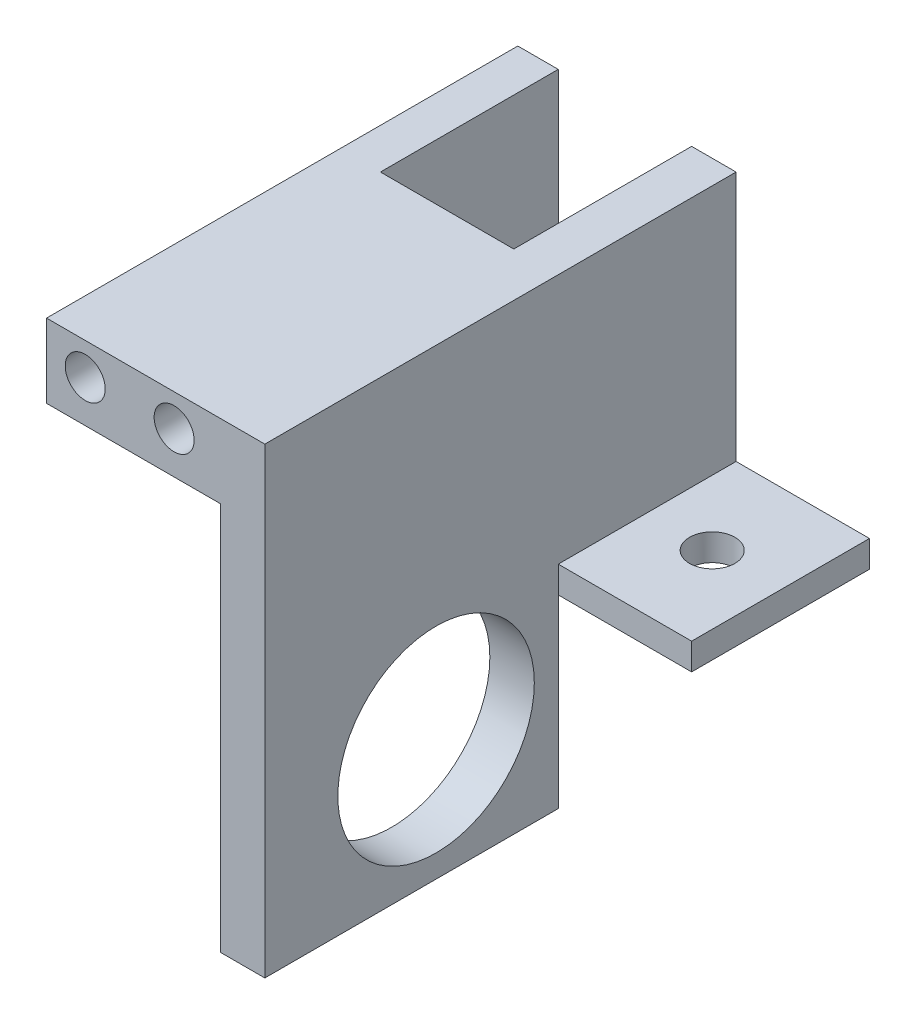
SolidWorks part; units mm, degrees
ref_plane "前视基准面" through (0, 0, 0) normal (0, 0, 1) x (1, 0, 0)
ref_plane "上视基准面" through (0, 0, 0) normal (0, 1, 0) x (1, 0, 0)
ref_plane "右视基准面" through (0, 0, 0) normal (1, 0, 0) x (0, 0, -1)
other "Configuration Table"
sketch "草图1" plane through (0, 0, 0) normal (0, 0, 1) x (1, 0, 0)
  line L1 (-11.1667, -5) -> (11.1667, -5)
  line L2 (-11.1667, -5) -> (-11.1667, 5)
  line L3 (-11.1667, 5) -> (11.1667, 5)
  line L4 (11.1667, -5) -> (11.1667, 5)
  line L5 (-11.1667, -5) -> (11.1667, 5) construction
  line L6 (-11.1667, 5) -> (11.1667, -5) construction
  point P0 (0, 0)
  dimension "D1" = 10
extrude "凸台-拉伸1" add sketch "草图1" along normal blind 30
sketch "草图2" plane through (0, -5, 0) normal (0, -1, 0) x (1, 0, 0)
  line L0 (-10.0833, 30.4566) -> (-10.0833, 0)
  line L1 (-10.0833, 30) -> (-10.0833, 38.1808) construction
  line L2 (-11.1667, 0) -> (11.1667, 0) construction
sketch "草图3" plane through (0, 0, 30) normal (0, 0, 1) x (1, 0, 0)
  line L0 (-9.2333, 0.05) -> (-9.2333, -5.0113)
  line L2 (9.4667, -5) -> (9.4667, 0.05)
  circle A0 centre (5.1167, -0.3) radius 2.25
  circle A1 centre (-4.8833, -0.3) radius 2.25
  arc A3 (9.4667, 0.05) -> (7.4667, 2.05) centre (7.4667, 0.05) ccw
  arc A4 (-9.2333, 0.05) -> (-6.4511, 1.8907) centre (-7.2333, 0.05) cw
sketch "草图4" plane through (0, -5, 0) normal (0, -1, 0) x (1, 0, 0)
  line L1 (-11.1667, 30) -> (-10.0833, 30)
  line L2 (-11.1667, 30) -> (-11.1667, 0)
  line L3 (-11.1667, 0) -> (-10.0833, 0)
  line L4 (-10.0833, 30) -> (-10.0833, 0)
extrude "切除-拉伸1" cut sketch "草图4" against normal blind 30
extrude "切除-拉伸2" cut sketch "草图3" against normal blind 15 contours A1 | A0
sketch "草图5" plane through (0, 0, 30) normal (0, 0, 1) x (1, 0, 0)
  line L0 (9.4667, -5) -> (9.4667, 0.05) construction
  line L1 (-9.2333, -5.0113) -> (9.4667, -5.0113)
  line L2 (-9.2333, -5.0113) -> (-9.2333, 3.3044)
  line L3 (-9.2333, 3.3044) -> (9.4667, 3.3044)
  line L4 (9.4667, -5.0113) -> (9.4667, 3.3044)
extrude "切除-拉伸3" cut sketch "草图5" against normal blind 30 flip side to cut
sketch "草图6" plane through (9.4667, 0, 0) normal (1, 0, 0) x (0, 0, -1)
  line L0 (22.3266, -2.313) -> (13.2059, -2.313) construction
sketch "草图7" plane through (0, 3.3044, 0) normal (0, 1, 0) x (1, 0, 0)
  arc A0 (-18.3547, 13) -> (-15.8066, 10.45) centre (-15.8066, 12.9981) cw
sketch "草图10" plane through (0, 0, 0) normal (0, 0, -1) x (-1, 0, 0)
  line L4 (-9.4667, -5) -> (9.2333, -5)
  line L5 (9.2333, -5) -> (9.2333, 3.3044)
  line L6 (9.2333, 3.3044) -> (-9.4667, 3.3044)
  line L7 (-9.4667, 3.3044) -> (-9.4667, -5)
  line L8 (-9.4667, -5) -> (9.2333, -5)
  line L9 (9.2333, -5) -> (9.2333, 3.3044)
  line L10 (9.2333, 3.3044) -> (-9.4667, 3.3044)
  line L11 (-9.4667, 3.3044) -> (-9.4667, -5)
  dimension "D1" = 0
extrude "凸台-拉伸2" add sketch "草图10" along normal blind 18
sketch "草图11" plane through (9.4667, 0, 0) normal (1, 0, 0) x (0, 0, -1)
  line L1 (18, -5) -> (-2, -5)
  line L2 (18, -5) -> (18, -2.313)
  line L3 (18, -2.313) -> (-2, -2.313)
  line L4 (-2, -5) -> (-2, -2.313)
  dimension "D1" = 20
extrude "切除-拉伸5" cut sketch "草图11" against normal through all
sketch "草图12" plane through (0, -2.313, 0) normal (0, -1, 0) x (1, 0, 0)
  line L0 (-9.2333, -12.9981) -> (9.4667, -12.9981)
  line L1 (-9.2333, -18) -> (-9.2333, 2) construction
  line L2 (9.4667, -200022.3266) -> (9.4667, 199986.7941) construction
  circle A0 centre (-4.7333, -12.9981) radius 2.5481
  circle A1 centre (4.9667, -12.9981) radius 2.5481
  point P5 (-4.7333, -12.9981)
  point P8 (4.9667, -12.9981)
  point P11 (0.1167, -12.9981)
  dimension "D1" = 4.5
  dimension "D2" = 4.5
extrude "切除-拉伸6" cut sketch "草图12" against normal through all contours L0 A0 | L0 A0 | L0 A1 | L0 A1
sketch "草图13" plane through (0, 3.3044, 0) normal (0, 1, 0) x (1, 0, 0)
  line L0 (-9.2333, 18) -> (-9.2333, -30) construction
  line L1 (9.4667, 18) -> (-9.2333, 18)
  line L2 (9.4667, 18) -> (9.4667, 23)
  line L3 (9.4667, 23) -> (-9.2333, 23)
  line L4 (-9.2333, 18) -> (-9.2333, 23)
extrude "凸台-拉伸3" add sketch "草图13" against normal up to surface (5.6174 mm away) up to face at (-4.7333, -2.313, -15.5463)
sketch "草图14" plane through (0, 3.3044, 0) normal (0, 1, 0) x (1, 0, 0)
  line L1 (-4, -5.4) -> (4, -5.4)
  line L2 (-4, -5.4) -> (-4, -10.4)
  line L3 (-4, -10.4) -> (4, -10.4)
  line L4 (4, -5.4) -> (4, -10.4)
  dimension "D1" = 4
  dimension "D2" = 4
  dimension "D3" = 5.4
  dimension "D4" = 5
sketch "草图15" plane through (0, -5, 0) normal (0, -1, 0) x (1, 0, 0)
  line L1 (-9.2333, 2) -> (9.4667, 2)
  line L2 (-9.2333, 2) -> (-9.2333, -23)
  line L3 (-9.2333, -23) -> (9.4667, -23)
  line L4 (9.4667, 2) -> (9.4667, -23)
extrude "切除-拉伸7" cut sketch "草图15" against normal through all
sketch "草图16" plane through (0, 3.3044, 0) normal (0, 1, 0) x (1, 0, 0)
  line L0 (10.3167, -29.9) -> (10.3167, -1.7297)
sketch "草图17" plane through (0, 3.3044, 0) normal (0, 1, 0) x (1, 0, 0)
  line L0 (10.3167, -29.9) -> (10.3167, -1.7297) construction
  line L1 (9.4667, -2) -> (15.3167, -2)
  line L2 (9.4667, -2) -> (9.4667, -30)
  line L3 (9.4667, -30) -> (15.3167, -30)
  line L4 (15.3167, -2) -> (15.3167, -30)
  dimension "D1" = 5
sketch "草图18" plane through (9.4667, 0, 0) normal (1, 0, 0) x (0, 0, -1)
  line L4 (-2, -5) -> (-2, 3.3044)
  line L5 (-2, 3.3044) -> (-30, 3.3044)
  line L6 (-30, 3.3044) -> (-30, -5)
  line L7 (-30, -5) -> (-2, -5)
  line L8 (-2, -5) -> (-2, 3.3044)
  line L9 (-2, 3.3044) -> (-30, 3.3044)
  line L10 (-30, 3.3044) -> (-30, -5)
  line L11 (-30, -5) -> (-2, -5)
  dimension "D1" = 0
extrude "凸台-拉伸5" add sketch "草图18" along normal blind 0.85
sketch "草图20" plane through (0, 3.3044, 0) normal (0, 1, 0) x (1, 0, 0)
  line L1 (10.3167, -30) -> (15.3167, -30)
  line L2 (10.3167, -30) -> (10.3167, -2)
  line L3 (10.3167, -2) -> (15.3167, -2)
  line L4 (15.3167, -30) -> (15.3167, -2)
extrude "凸台-拉伸6" add sketch "草图20" against normal blind 52
sketch "草图22" plane through (15.3167, 0, 0) normal (1, 0, 0) x (0, 0, -1)
  circle A0 centre (-10.7419, -35.1) radius 10
  dimension "D1" = 20
sketch "草图23" plane through (0, 0, 2) normal (0, 0, -1) x (-1, 0, 0)
  line L6 (9.2333, 3.3044) -> (-15.3167, 3.3044)
  line L7 (-15.3167, 3.3044) -> (-15.3167, -48.6956)
  line L8 (-15.3167, -48.6956) -> (-10.3167, -48.6956)
  line L9 (-10.3167, -48.6956) -> (-10.3167, -5)
  line L10 (-10.3167, -5) -> (9.2333, -5)
  line L11 (9.2333, -5) -> (9.2333, 3.3044)
  line L12 (9.2333, 3.3044) -> (-15.3167, 3.3044)
  line L13 (-15.3167, 3.3044) -> (-15.3167, -48.6956)
  line L14 (-15.3167, -48.6956) -> (-10.3167, -48.6956)
  line L15 (-10.3167, -48.6956) -> (-10.3167, -5)
  line L16 (-10.3167, -5) -> (9.2333, -5)
  line L17 (9.2333, -5) -> (9.2333, 3.3044)
  dimension "D1" = 0
extrude "凸台-拉伸7" add sketch "草图23" along normal blind 5
extrude "切除-拉伸8" cut sketch "草图22" against normal through all contours A0
sketch "草图24" plane through (0, 0, -3) normal (0, 0, -1) x (-1, 0, 0)
  line L0 (-10.3167, -5) -> (-10.3167, 3.3044)
  line L6 (9.2333, -5) -> (9.2333, 3.3044)
  line L7 (9.2333, 3.3044) -> (-15.3167, 3.3044)
  line L8 (-15.3167, 3.3044) -> (-15.3167, -48.6956)
  line L9 (-15.3167, -48.6956) -> (-10.3167, -48.6956)
  line L10 (-10.3167, -48.6956) -> (-10.3167, -5)
  line L11 (-10.3167, -5) -> (9.2333, -5)
  line L13 (-10.3167, 3.3044) -> (-15.3167, 3.3044)
  line L14 (-15.3167, 3.3044) -> (-15.3167, -48.6956)
  line L15 (-15.3167, -48.6956) -> (-10.3167, -48.6956)
  line L16 (-10.3167, -48.6956) -> (-10.3167, -5)
  dimension "D1" = 0
extrude "凸台-拉伸8" add sketch "草图24" along normal blind 20
sketch "草图28" plane through (0, -48.6956, 0) normal (0, -1, 0) x (1, 0, 0)
  line L1 (10.3167, -3) -> (15.3167, -3)
  line L2 (10.3167, -3) -> (10.3167, -23)
  line L3 (10.3167, -23) -> (15.3167, -23)
  line L4 (15.3167, -3) -> (15.3167, -23)
sketch "草图29" plane through (0, 0, -23) normal (0, 0, -1) x (-1, 0, 0)
  line L0 (-21.3498, -27.8856) -> (-1.9409, -27.8856)
  line L1 (-9.4667, 3.3044) -> (-15.3167, 3.3044) construction
  dimension "D1" = 31.19
sketch "草图30" plane through (0, -48.6956, 0) normal (0, -1, 0) x (1, 0, 0)
  line L1 (10.3167, -23) -> (15.3167, -23)
  line L2 (10.3167, -23) -> (10.3167, -3)
  line L3 (10.3167, -3) -> (15.3167, -3)
  line L4 (15.3167, -23) -> (15.3167, -3)
extrude "切除-拉伸10" cut sketch "草图30" against normal up to vertex (20.81 mm away) up to point (21.3498, -27.8856, -23)
sketch "草图31" plane through (15.3167, 0, 0) normal (1, 0, 0) x (0, 0, -1)
  line L0 (23, 3.3044) -> (23, -27.8856) construction
  line L1 (3, -27.8856) -> (23, -27.8856)
  line L2 (3, -27.8856) -> (3, -24.8856)
  line L3 (3, -24.8856) -> (23, -24.8856)
  line L4 (23, -27.8856) -> (23, -24.8856)
  dimension "D1" = 3
extrude "凸台-拉伸9" add sketch "草图31" along normal blind 15 and the other way blind 20
sketch "草图32" plane through (0, -24.8856, 0) normal (0, 1, 0) x (1, 0, 0)
  line L0 (-4.6833, 13) -> (30.3167, 13)
  line L1 (-4.6833, 23) -> (-4.6833, 3) construction
  line L2 (30.3167, 23) -> (30.3167, 3) construction
  line L3 (12.8167, 3) -> (12.8167, 28.2983)
  line L4 (10.3167, 3) -> (15.3167, 3) construction
  circle A0 centre (3.0008, 13) radius 2.55
  circle A1 centre (22.6325, 13) radius 2.55
  dimension "D1" = 5.1
extrude "切除-拉伸11" cut sketch "草图32" against normal through all contours A0 | A1
sketch "草图33" plane through (0, 3.3044, 0) normal (0, 1, 0) x (1, 0, 0)
  line L1 (-9.2333, 3) -> (-4.6833, 3)
  line L2 (-9.2333, 3) -> (-9.2333, 23)
  line L3 (-9.2333, 23) -> (-4.6833, 23)
  line L4 (-4.6833, 3) -> (-4.6833, 23)
extrude "凸台-拉伸10" add sketch "草图33" against normal up to surface (31.19 mm away) up to face at (12.8167, -27.8856, -9.6667)
sketch "草图34" plane through (15.3167, 0, 0) normal (1, 0, 0) x (0, 0, -1)
  circle A0 centre (-10.7419, -35.1) radius 11.05
  dimension "D1" = 22.1
extrude "切除-拉伸12" cut sketch "草图34" against normal blind 10
